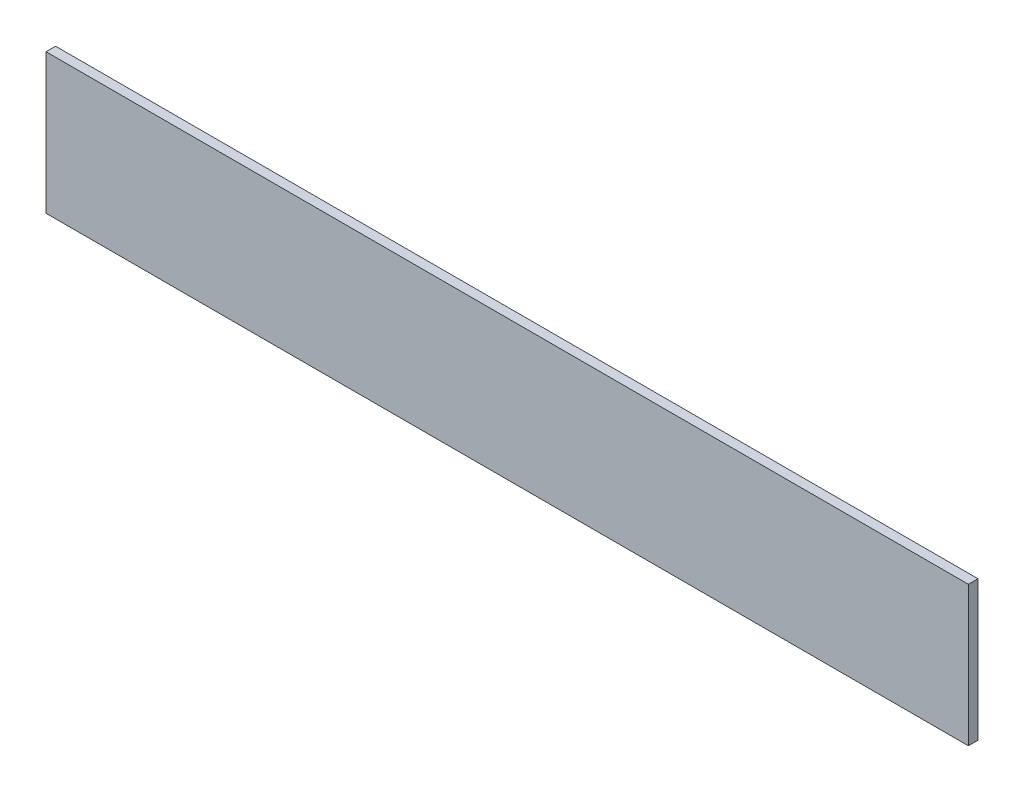
SolidWorks part; units mm, degrees
ref_plane "Front Plane" through (0, 0, 0) normal (0, 0, 1) x (1, 0, 0)
ref_plane "Top Plane" through (0, 0, 0) normal (0, 1, 0) x (1, 0, 0)
ref_plane "Right Plane" through (0, 0, 0) normal (1, 0, 0) x (0, 0, -1)
sketch "Sketch1" plane through (0, 0, 0) normal (0, 0, 1) x (1, 0, 0)
  line L1 (-609.6, -92.456) -> (609.6, -92.456)
  line L2 (-609.6, -92.456) -> (-609.6, 92.456)
  line L3 (-609.6, 92.456) -> (609.6, 92.456)
  line L4 (609.6, -92.456) -> (609.6, 92.456)
  line L5 (-609.6, -92.456) -> (609.6, 92.456) construction
  line L6 (-609.6, 92.456) -> (609.6, -92.456) construction
  point P0 (0, 0)
  dimension "D1" = 184.912
  dimension "D2" = 1219.2
extrude "Boss-Extrude2" add sketch "Sketch1" along normal blind 12.7
